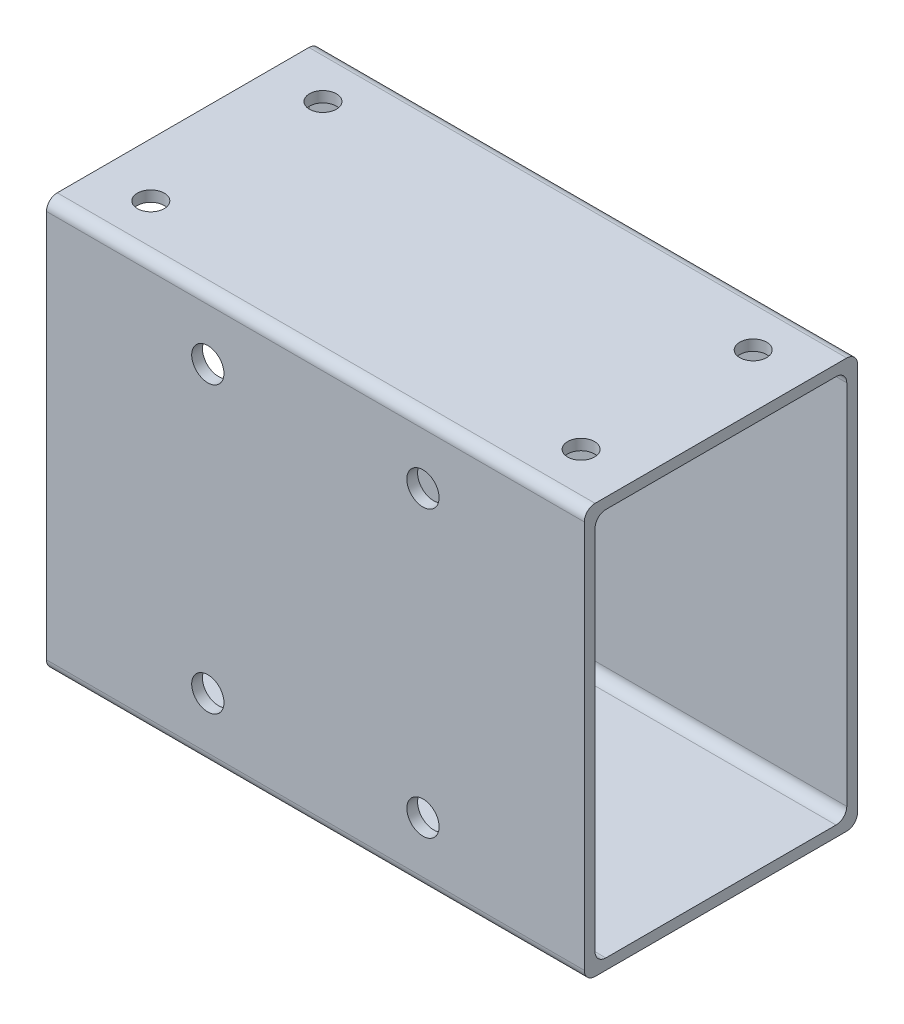
SolidWorks part; units mm, degrees
material "A500"
ref_plane "Alzado" through (0, 0, 0) normal (0, 0, 1) x (1, 0, 0)
ref_plane "Planta" through (0, 0, 0) normal (0, 1, 0) x (1, 0, 0)
ref_plane "Vista lateral" through (0, 0, 0) normal (1, 0, 0) x (0, 0, -1)
sketch "Sketch1" plane through (0, 0, 0) normal (1, 0, 0) x (0, 0, -1)
  line L1 (25.4, 38.1) -> (-25.4, 38.1)
  line L2 (25.4, 38.1) -> (25.4, -38.1)
  line L3 (25.4, -38.1) -> (-25.4, -38.1)
  line L4 (-25.4, 38.1) -> (-25.4, -38.1)
  line L5 (25.4, 38.1) -> (-25.4, -38.1) construction
  line L6 (25.4, -38.1) -> (-25.4, 38.1) construction
  point P0 (0, 0)
  dimension "D1" = 76.2
  dimension "D2" = 50.8
extrude "Boss-Extrude1" add sketch "Sketch1" against normal blind 100
sketch "Sketch2" plane through (0, 0, 0) normal (1, 0, 0) x (0, 0, -1)
  line L0 (25.4, 38.1) -> (-25.4, 38.1) construction
  line L1 (23.4, 36.1) -> (-23.4, 36.1)
  line L2 (23.4, 36.1) -> (23.4, -36.1)
  line L3 (23.4, -36.1) -> (-23.4, -36.1)
  line L4 (-23.4, 36.1) -> (-23.4, -36.1)
  line L5 (23.4, 36.1) -> (-23.4, -36.1) construction
  line L6 (23.4, -36.1) -> (-23.4, 36.1) construction
  line L7 (25.4, -38.1) -> (25.4, 38.1) construction
  point P0 (0, 0)
  dimension "D1" = 2
  dimension "D2" = 2
extrude "Cut-Extrude1" cut sketch "Sketch2" against normal through all
fillet "Fillet2" radius 2 8 edges at (-50, -38.1, -25.4) (-50, -38.1, 25.4) (-50, 38.1, 25.4) (-50, 38.1, -25.4) (-50, -36.1, -23.4) (-50, 36.1, -23.4) (-50, -36.1, 23.4) (-50, 36.1, 23.4)
sketch "Croquis2" plane through (0, 0, 25.4) normal (0, 0, 1) x (1, 0, 0)
  line L0 (-50, 36.1) -> (-50, -36.1) construction
  line L1 (0, 36.1) -> (-100, 36.1) construction
  line L2 (-100, -36.1) -> (0, -36.1) construction
  line L4 (-30, 26.5) -> (-70, 26.5)
  line L5 (-30, 26.5) -> (-30, -26.5)
  line L6 (-30, -26.5) -> (-70, -26.5)
  line L7 (-70, 26.5) -> (-70, -26.5)
  line L8 (-30, 26.5) -> (-70, -26.5) construction
  line L9 (-30, -26.5) -> (-70, 26.5) construction
  circle A0 centre (-70, 26.5) radius 3
  circle A1 centre (-30, 26.5) radius 3
  circle A2 centre (-30, -26.5) radius 3
  circle A3 centre (-70, -26.5) radius 3
  point P6 (-50, 0)
  dimension "D3" = 6
  dimension "D4" = 6
  dimension "D5" = 6
  dimension "D6" = 6
  dimension "D1" = 53
  dimension "D2" = 40
extrude "Cortar-Extruir2" cut sketch "Croquis2" against normal blind 10 contours L5 A1 L4 | L4 A1 L5 | L4 A0 L7 | L7 A0 L4 | L6 A3 L7 | L7 A3 L6 | L6 A2 L5 | L5 A2 L6
sketch "Croquis4" plane through (0, 0, -25.4) normal (0, 0, -1) x (-1, 0, 0)
  line L0 (49.2, 38.1) -> (49.2, -38.1) construction
  line L2 (0, 38.1) -> (100, 38.1) construction
  line L3 (100, -38.1) -> (0, -38.1) construction
  line L6 (100, -36.1) -> (100, 36.1) construction
  line L7 (100, 23.1) -> (49.2, 23.1) construction
  line L8 (100, -23.1) -> (49.2, -23.1) construction
  line L9 (49.2, 0) -> (100, 0) construction
  circle A1 centre (90, 23.1) radius 2.5
  circle A2 centre (59.2, 23.1) radius 2.5
  circle A3 centre (59.2, -23.1) radius 2.5
  circle A4 centre (90, -23.1) radius 2.5
  circle A5 centre (74.6, 0) radius 2.5
  dimension "D3" = 15
  dimension "D4" = 5
  dimension "D5" = 5
  dimension "D6" = 5
  dimension "D7" = 5
  dimension "D8" = 5
  dimension "D1" = 50.8
  dimension "D2" = 15
  dimension "D9" = 10
  dimension "D10" = 10
  dimension "D11" = 10
  dimension "D12" = 10
extrude "Cortar-Extruir5" [suppressed] cut sketch "Croquis4" against normal blind 10
sketch "Croquis6" plane through (0, 0, -25.4) normal (0, 0, -1) x (-1, 0, 0)
  line L0 (49.2, 38.1) -> (49.2, -38.1) construction
  line L8 (0, 0) -> (41.2, 0) construction
  line L9 (41.2, 20) -> (17.2, 20)
  line L10 (41.2, 20) -> (41.2, -20)
  line L11 (41.2, -20) -> (17.2, -20)
  line L12 (17.2, 20) -> (17.2, -20)
  line L13 (0, -36.1) -> (0, 36.1) construction
  line L14 (0, 38.1) -> (100, 38.1) construction
  line L15 (100, -38.1) -> (0, -38.1) construction
  line L16 (100, -36.1) -> (100, 36.1) construction
  circle A0 centre (17.2, 20) radius 2.5
  circle A1 centre (17.2, -20) radius 2.5
  circle A2 centre (41.2, -20) radius 2.5
  circle A3 centre (41.2, 20) radius 2.5
  dimension "D5" = 5
  dimension "D6" = 5
  dimension "D7" = 5
  dimension "D8" = 5
  dimension "D1" = 8
  dimension "D2" = 24
  dimension "D3" = 40
  dimension "D4" = 20
  dimension "D9" = 50.8
extrude "Cortar-Extruir6" [suppressed] cut sketch "Croquis6" against normal blind 10 contours A0 | A3 | A2 | A1
sketch "Croquis7" plane through (0, -38.1, 0) normal (0, -1, 0) x (1, 0, 0)
  line L0 (0, 0.4) -> (-100, 0.4) construction
  line L1 (0, 23.4) -> (0, -23.4) construction
  line L2 (-100, 23.4) -> (-100, -23.4) construction
  line L3 (-100, 25.4) -> (0, 25.4) construction
  circle A0 centre (-15, 0.4) radius 2.5
  circle A1 centre (-85, 0.4) radius 2.5
  dimension "D2" = 5
  dimension "D5" = 5
  dimension "D1" = 25
  dimension "D3" = 15
  dimension "D4" = 15
extrude "Cortar-Extruir7" [suppressed] cut sketch "Croquis7" against normal blind 10
sketch "Croquis8" plane through (0, 38.1, 0) normal (0, 1, 0) x (1, 0, 0)
  line L0 (-100, 0) -> (0, 0) construction
  line L1 (-100, 23.4) -> (-100, -23.4) construction
  line L3 (-10, 16) -> (-90, 16)
  line L4 (-10, 16) -> (-10, -16)
  line L5 (-10, -16) -> (-90, -16)
  line L6 (-90, 16) -> (-90, -16)
  line L7 (-10, 16) -> (-90, -16) construction
  line L8 (-10, -16) -> (-90, 16) construction
  circle A0 centre (-90, 16) radius 2.5
  circle A1 centre (-10, 16) radius 2.5
  circle A2 centre (-90, -16) radius 2.5
  circle A3 centre (-10, -16) radius 2.5
  point P5 (-50, 0)
  dimension "D3" = 5
  dimension "D4" = 5
  dimension "D5" = 5
  dimension "D6" = 5
  dimension "D1" = 80
  dimension "D2" = 32
extrude "Cortar-Extruir8" cut sketch "Croquis8" against normal blind 10 contours A0 | A2 | A1 | A3
